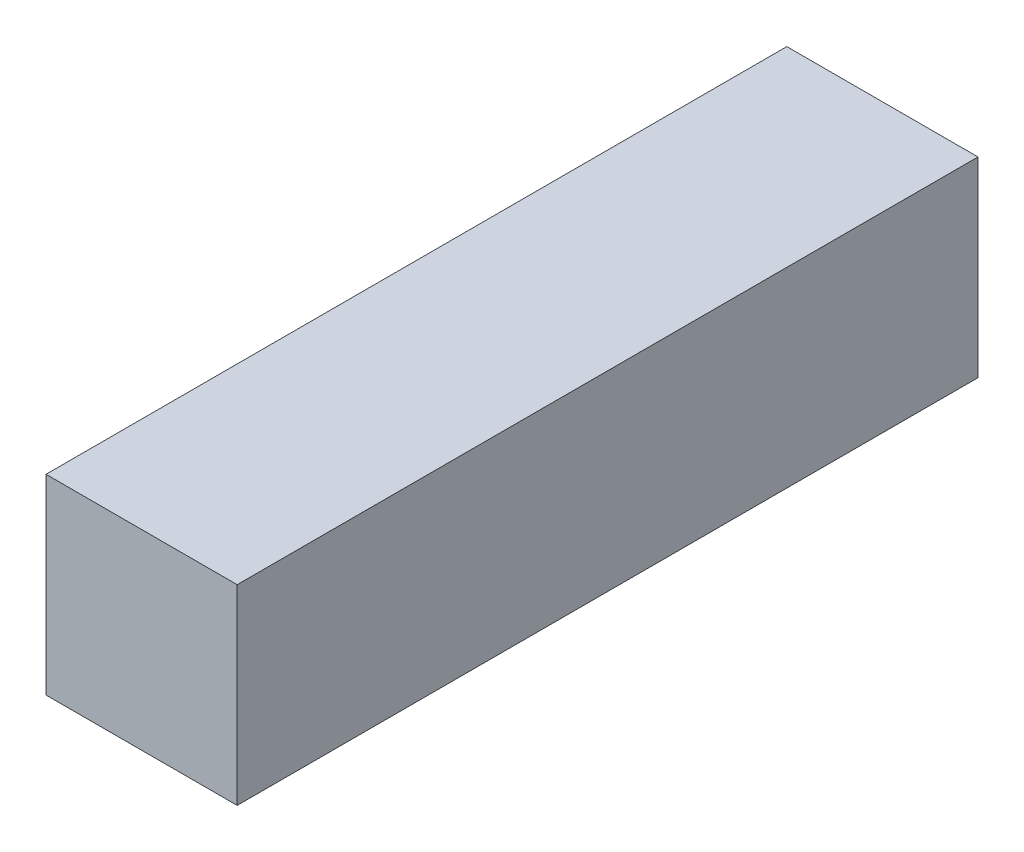
SolidWorks part; units mm, degrees
material "6061 Alloy"
ref_plane "Front Plane" through (0, 0, 0) normal (0, 0, 1) x (1, 0, 0)
ref_plane "Top Plane" through (0, 0, 0) normal (0, 1, 0) x (1, 0, 0)
ref_plane "Right Plane" through (0, 0, 0) normal (1, 0, 0) x (0, 0, -1)
sketch "Sketch1" plane through (0, 0, 0) normal (0, 1, 0) x (1, 0, 0)
  line L0 (-1, -7.25) -> (1, -7.25)
  line L1 (1, -7.25) -> (1, 7.25)
  line L2 (-2, 7.25) -> (-1, 7.25)
  line L3 (-1, 7.25) -> (-1, -7.25)
  line L4 (2, -7.25) -> (2, 7.25)
  line L5 (-2, 7.25) -> (-2, -8.25)
  line L6 (-2, -8.25) -> (1, -8.25)
  line L7 (2, -7.25) -> (2, -8.25)
  line L8 (2, -8.25) -> (1, -8.25)
  line L9 (1, 7.25) -> (2, 7.25)
  dimension "D1" = 1
  dimension "D2" = 1
extrude "Boss-Extrude1" add sketch "Sketch1" along normal blind 3
sketch "Sketch2" plane through (0, 3, 0) normal (0, 1, 0) x (1, 0, 0)
  line L0 (-2, 7.25) -> (2, 7.25)
  line L1 (2, 7.25) -> (2, -8.25)
  line L2 (2, -8.25) -> (-2, -8.25)
  line L3 (-2, -8.25) -> (-2, 7.25)
extrude "Boss-Extrude2" add sketch "Sketch2" along normal blind 1
sketch "Sketch3" plane through (0, 0, 0) normal (0, -1, 0) x (1, 0, 0)
  line L0 (-1, 7.25) -> (1, 7.25)
  line L1 (1, 7.25) -> (1, -7.25)
  line L2 (1, -7.25) -> (1.5, -7.25)
  line L3 (2, -7.25) -> (1, -7.25) construction
  line L4 (-1, 7.25) -> (-1, -7.25)
  line L5 (-1, -7.25) -> (-1.5, -7.25)
  line L6 (-1, -7.25) -> (-2, -7.25) construction
  line L7 (-1.5, -7.25) -> (-1.5, 7.7172)
  line L8 (-1.5, 7.7172) -> (1.5, 7.7172)
  line L9 (1.5, 7.7172) -> (1.5, -7.25)
extrude "Cut-Extrude1" cut sketch "Sketch3" against normal blind 0.25
